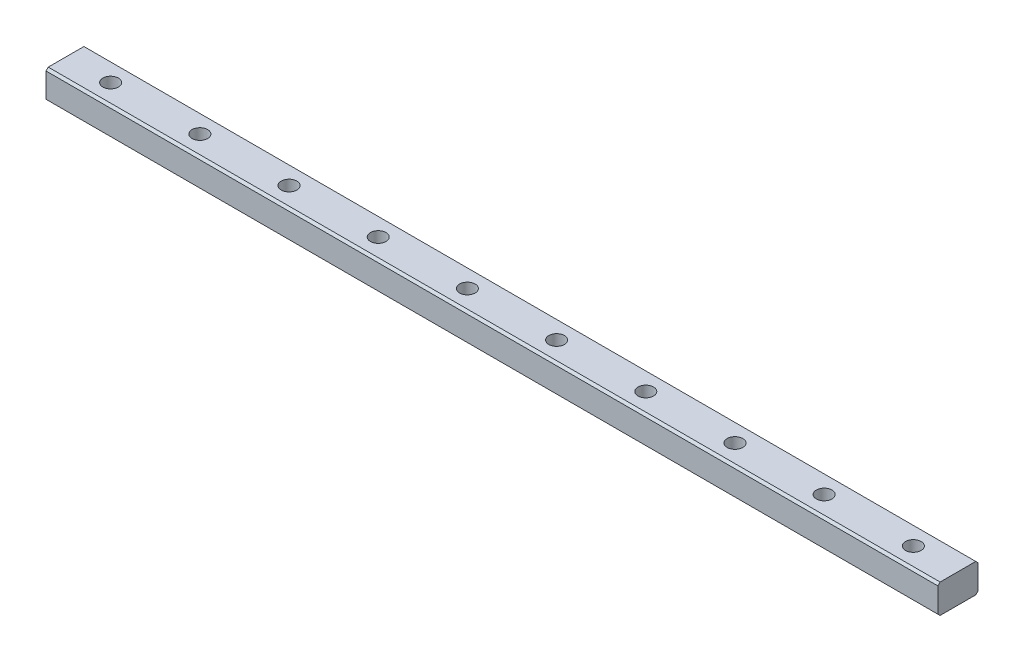
SolidWorks part; units mm, degrees
material "铸造合金钢"
ref_plane "前视基准面" through (0, 0, 0) normal (0, 0, 1) x (1, 0, 0)
ref_plane "上视基准面" through (0, 0, 0) normal (0, 1, 0) x (1, 0, 0)
ref_plane "右视基准面" through (0, 0, 0) normal (1, 0, 0) x (0, 0, -1)
sketch "草图1" plane through (0, 0, 0) normal (1, 0, 0) x (0, 0, -1)
  line L1 (4.5, -3.25) -> (-4.5, -3.25)
  line L2 (4.5, -3.25) -> (4.5, 3.25)
  line L3 (4.5, 3.25) -> (-4.5, 3.25)
  line L4 (-4.5, -3.25) -> (-4.5, 3.25)
  line L5 (4.5, -3.25) -> (-4.5, 3.25) construction
  line L6 (4.5, 3.25) -> (-4.5, -3.25) construction
  point P0 (0, 0)
  dimension "D1" = 9
  dimension "D2" = 6.5
extrude "拉伸1" add sketch "草图1" along normal blind 200
sketch "草图2" plane through (0, -3.25, 0) normal (0, -1, 0) x (1, 0, 0)
  line L0 (0, 4.5) -> (0, -4.5) construction
  circle A0 centre (10, 0) radius 1.75
  circle A1 centre (170, 0) radius 1.75
  circle A2 centre (190, 0) radius 1.75
  circle A3 centre (210, 0) radius 1.75
  circle A4 centre (230, 0) radius 1.75
  circle A5 centre (250, 0) radius 1.75
  circle A6 centre (270, 0) radius 1.75
  circle A7 centre (290, 0) radius 1.75
  circle A50 centre (30, 0) radius 1.75
  circle A51 centre (50, 0) radius 1.75
  circle A52 centre (70, 0) radius 1.75
  circle A53 centre (90, 0) radius 1.75
  circle A54 centre (110, 0) radius 1.75
  circle A55 centre (130, 0) radius 1.75
  circle A56 centre (150, 0) radius 1.75
  dimension "D1" = 10
  dimension "D2" = 3.5
  dimension "D3" = 15
extrude "拉伸2" cut sketch "草图2" against normal blind 8
sketch "草图3" plane through (0, -3.25, 0) normal (0, -1, 0) x (1, 0, 0)
  circle A0 centre (10, 0) radius 3
  circle A1 centre (10, 0) radius 1.75 construction
  circle A2 centre (170, 0) radius 3
  circle A3 centre (190, 0) radius 3
  circle A4 centre (210, 0) radius 3
  circle A5 centre (230, 0) radius 3
  circle A6 centre (250, 0) radius 3
  circle A7 centre (270, 0) radius 3
  circle A8 centre (290, 0) radius 3
  circle A51 centre (30, 0) radius 3
  circle A52 centre (50, 0) radius 3
  circle A53 centre (70, 0) radius 3
  circle A54 centre (90, 0) radius 3
  circle A55 centre (110, 0) radius 3
  circle A56 centre (130, 0) radius 3
  circle A57 centre (150, 0) radius 3
  dimension "D1" = 6
  dimension "D2" = 15
extrude "拉伸3" cut sketch "草图3" against normal blind 3.5
chamfer "倒角1" distance 0.5 angle 45 4 edges at (100, -3.25, 4.5) (100, 3.25, 4.5) (100, 3.25, -4.5) (100, -3.25, -4.5)
